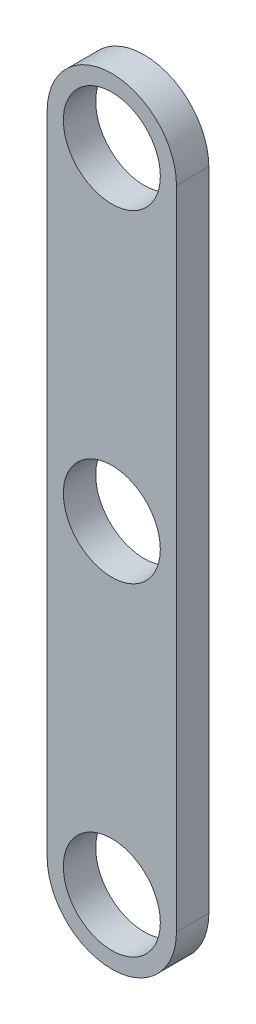
SolidWorks part; units mm, degrees
ref_plane "Front Plane" through (0, 0, 0) normal (0, 0, 1) x (1, 0, 0)
ref_plane "Top Plane" through (0, 0, 0) normal (0, 1, 0) x (1, 0, 0)
ref_plane "Right Plane" through (0, 0, 0) normal (1, 0, 0) x (0, 0, -1)
sketch "Sketch2" plane through (0, 0, 0) normal (0, 0, 1) x (1, 0, 0)
  line L0 (0, 0) -> (0, 100) construction
  line L1 (-10, 0) -> (-10, 100)
  line L2 (10, 0) -> (10, 100)
  arc A0 (-10, 0) -> (10, 0) centre (0, 0) ccw
  arc A1 (10, 100) -> (-10, 100) centre (0, 100) ccw
  circle A2 centre (0, 100) radius 7.5
  circle A3 centre (0, 0) radius 7.5
  circle A4 centre (0, 50) radius 7.5
  point P3 (0, 50)
  dimension "D3" = 15
  dimension "D1" = 100
  dimension "D2" = 20
extrude "Boss-Extrude1" add sketch "Sketch2" along normal blind 5
